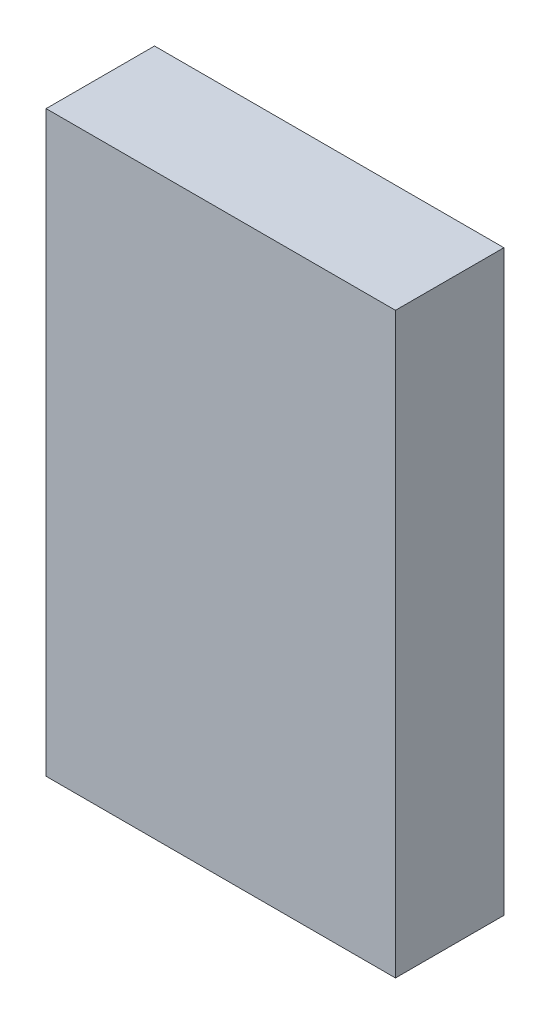
SolidWorks part; units mm, degrees
ref_plane "Front Plane" through (0, 0, 0) normal (0, 0, 1) x (1, 0, 0)
ref_plane "Top Plane" through (0, 0, 0) normal (0, 1, 0) x (1, 0, 0)
ref_plane "Right Plane" through (0, 0, 0) normal (1, 0, 0) x (0, 0, -1)
sketch "Sketch1" plane through (0, 0, 0) normal (0, 0, 1) x (1, 0, 0)
  line L1 (-36.83, -60.96) -> (36.83, -60.96)
  line L2 (-36.83, -60.96) -> (-36.83, 60.96)
  line L3 (-36.83, 60.96) -> (36.83, 60.96)
  line L4 (36.83, -60.96) -> (36.83, 60.96)
  line L5 (-36.83, -60.96) -> (36.83, 60.96) construction
  line L6 (-36.83, 60.96) -> (36.83, -60.96) construction
  point P0 (0, 0)
  dimension "D1" = 73.66
  dimension "D2" = 121.92
extrude "Boss-Extrude1" add sketch "Sketch1" along normal blind 22.86
